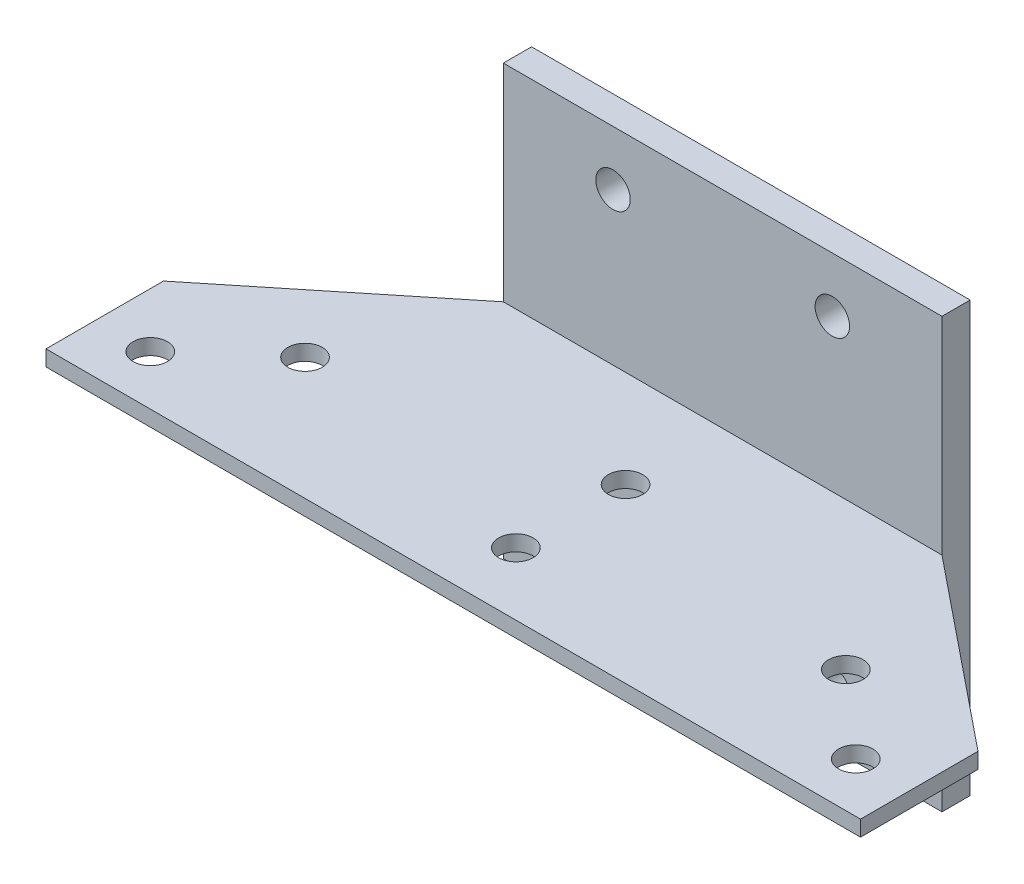
SolidWorks part; units mm, degrees
ref_plane "前视基准面" through (0, 0, 0) normal (0, 0, 1) x (1, 0, 0)
ref_plane "上视基准面" through (0, 0, 0) normal (0, 1, 0) x (1, 0, 0)
ref_plane "右视基准面" through (0, 0, 0) normal (1, 0, 0) x (0, 0, -1)
sketch "草图1" plane through (0, 0, 0) normal (0, 0, 1) x (1, 0, 0)
  line L1 (0, 0) -> (280, 0)
  line L2 (0, 0) -> (0, 274)
  line L3 (0, 274) -> (280, 274)
  line L4 (280, 0) -> (280, 274)
  dimension "D1" = 280
  dimension "D2" = 274
extrude "拉伸1" add sketch "草图1" along normal blind 18
sketch "草图2" plane through (0, 0, 18) normal (0, 0, 1) x (1, 0, 0)
  line L0 (0, 274) -> (0, 0) construction
  line L1 (-120, 142) -> (400, 142)
  line L2 (-120, 142) -> (-120, 132)
  line L3 (-120, 132) -> (400, 132)
  line L4 (400, 142) -> (400, 132)
  line L5 (280, 274) -> (0, 274) construction
  dimension "D1" = 10
  dimension "D2" = 520
  dimension "D3" = 120
  dimension "D4" = 132
extrude "拉伸2" add sketch "草图2" along normal blind 172
sketch "草图3" plane through (0, 132, 0) normal (0, -1, 0) x (1, 0, 0)
  line L0 (0, 18) -> (-120, 115)
  line L1 (-120, 190) -> (400, 190) construction
  line L2 (-120, 115) -> (-120, 18)
  line L3 (-120, 18) -> (0, 18)
  dimension "D1" = 75
extrude "切除-拉伸1" cut sketch "草图3" against normal through all
sketch "草图4" plane through (0, 132, 0) normal (0, -1, 0) x (1, 0, 0)
  line L0 (400, 115) -> (280, 18)
  line L1 (-120, 190) -> (400, 190) construction
  line L2 (280, 18) -> (400, 18)
  line L3 (400, 115) -> (400, 18)
  dimension "D1" = 75
extrude "切除-拉伸2" cut sketch "草图4" against normal through all
sketch "草图5" plane through (0, 0, 0) normal (0, 0, -1) x (-1, 0, 0)
  line L0 (-280, 0) -> (-280, 274) construction
  line L1 (0, 0) -> (-280, 0) construction
  circle A0 centre (-210, 35) radius 11
  dimension "D1" = 70
  dimension "D2" = 35
extrude "切除-拉伸3" cut sketch "草图5" against normal through all
sketch "草图6" plane through (0, 0, 0) normal (0, 0, -1) x (-1, 0, 0)
  line L0 (-280, 0) -> (-280, 274) construction
  line L1 (-280, 274) -> (0, 274) construction
  circle A0 centre (-210, 239) radius 11
  dimension "D1" = 70
  dimension "D2" = 35
extrude "切除-拉伸4" cut sketch "草图6" against normal through all
sketch "草图7" plane through (0, 0, 0) normal (0, 0, -1) x (-1, 0, 0)
  line L0 (0, 274) -> (0, 0) construction
  line L1 (0, 0) -> (-280, 0) construction
  circle A0 centre (-70, 35) radius 11
  dimension "D1" = 70
  dimension "D2" = 35
extrude "切除-拉伸5" cut sketch "草图7" against normal through all
sketch "草图8" plane through (0, 0, 0) normal (0, 0, -1) x (-1, 0, 0)
  line L0 (-280, 274) -> (0, 274) construction
  line L1 (0, 274) -> (0, 0) construction
  circle A0 centre (-70, 239) radius 11
  dimension "D1" = 35
  dimension "D2" = 70
extrude "切除-拉伸6" cut sketch "草图8" against normal through all
sketch "草图9" plane through (0, 132, 0) normal (0, -1, 0) x (1, 0, 0)
  line L0 (140, -838.8302) -> (140, 49161.1698) construction
  line L1 (400, 190) -> (400, 115) construction
  line L2 (0, 18) -> (280, 18) construction
  circle A0 centre (140, 80) radius 11
  circle A1 centre (140, 150) radius 11
  circle A2 centre (-85.1891, 158.2411) radius 11
  circle A3 centre (-32.6366, 112) radius 11
  circle A4 centre (365.1891, 158.2411) radius 11
  circle A5 centre (312.6366, 112) radius 11
  dimension "D2" = 62
  dimension "D3" = 70
  dimension "D1" = 260
  dimension "D4" = 94
  dimension "D5" = 70
  dimension "D6" = 172.6366
  dimension "D7" = 52.5525
  dimension "D8" = 172.6366
  dimension "D9" = 52.5525
extrude "切除-拉伸8" cut sketch "草图9" against normal through all
